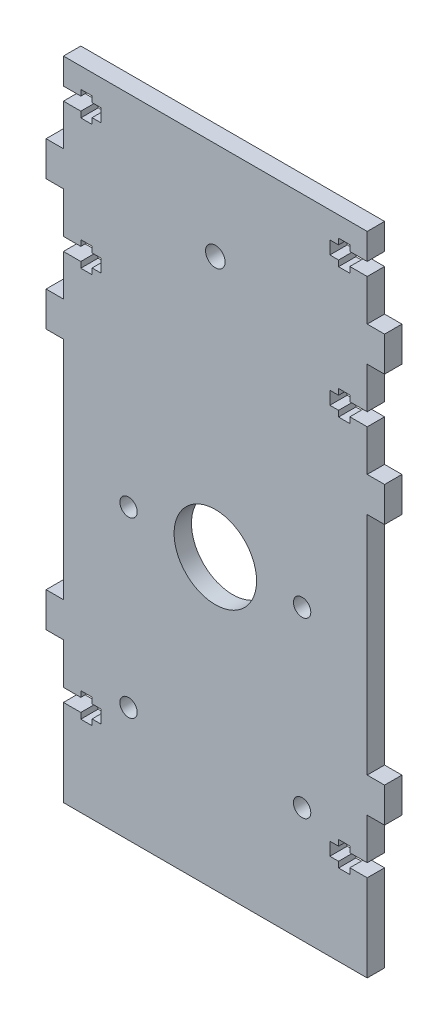
SolidWorks part; units mm, degrees
ref_plane "前视基准面" through (0, 0, 0) normal (0, 0, 1) x (1, 0, 0)
ref_plane "上视基准面" through (0, 0, 0) normal (0, 1, 0) x (1, 0, 0)
ref_plane "右视基准面" through (0, 0, 0) normal (1, 0, 0) x (0, 0, -1)
sketch "草图1" plane through (0, 0, 0) normal (0, 0, 1) x (1, 0, 0)
  line L1 (0, 4.863) -> (-4, 4.863)
  line L2 (-4, 4.863) -> (-4, 12.863)
  line L3 (-4, 12.863) -> (0, 12.863)
  line L5 (0, 22.363) -> (4, 22.363)
  line L6 (4, 22.363) -> (4, 21.013)
  line L7 (4, 21.013) -> (6.6, 21.013)
  line L8 (6.6, 21.013) -> (6.6, 22.363)
  line L9 (6.6, 22.363) -> (8.6, 22.363)
  line L10 (8.6, 22.363) -> (8.6, 25.363)
  line L11 (8.6, 25.363) -> (6.6, 25.363)
  line L12 (6.6, 25.363) -> (6.6, 26.713)
  line L13 (6.6, 26.713) -> (4, 26.713)
  line L14 (4, 26.713) -> (4, 25.363)
  line L15 (4, 25.363) -> (0, 25.363)
  line L16 (0, 25.363) -> (0, 31.363)
  line L17 (0, 31.363) -> (70, 31.363)
  line L18 (0, 25.363) -> (0, 22.363) construction
  line L20 (35, 31.363) -> (35, 28.363) construction
  line L21 (-4, -21.137) -> (0, -21.137) construction
  line L39 (-4, 8.863) -> (74, 8.863) construction
  line L40 (8.6, 23.863) -> (0, 23.863) construction
  line L51 (0, -7.637) -> (0, -4.637) construction
  line L52 (4, -7.637) -> (0, -7.637)
  line L53 (4, -8.987) -> (4, -7.637)
  line L54 (6.6, -8.987) -> (4, -8.987)
  line L55 (6.6, -7.637) -> (6.6, -8.987)
  line L56 (8.6, -7.637) -> (6.6, -7.637)
  line L57 (8.6, -4.637) -> (8.6, -7.637)
  line L58 (6.6, -4.637) -> (8.6, -4.637)
  line L59 (6.6, -3.287) -> (6.6, -4.637)
  line L60 (4, -3.287) -> (6.6, -3.287)
  line L61 (4, -4.637) -> (4, -3.287)
  line L62 (0, -4.637) -> (4, -4.637)
  line L63 (0, -4.637) -> (0, 4.863)
  line L65 (70, -51.137) -> (0, -51.137) construction
  line L83 (0, 22.363) -> (0, 12.863)
  line L84 (8.6, -6.137) -> (6.1425, -6.137) construction
  line L91 (-4, -25.137) -> (0, -25.137)
  line L92 (-4, -17.137) -> (-4, -25.137)
  line L93 (0, -17.137) -> (-4, -17.137)
  line L94 (0, -17.137) -> (0, -7.637)
  line L95 (0, -97.637) -> (4, -97.637)
  line L96 (4, -97.637) -> (4, -98.987)
  line L97 (70, 25.363) -> (70, 31.363)
  line L98 (63.4, 25.363) -> (63.4, 26.713)
  line L99 (63.4, 21.013) -> (63.4, 22.363)
  line L100 (66, 26.713) -> (66, 25.363)
  line L101 (66, 22.363) -> (66, 21.013)
  line L102 (66, 25.363) -> (70, 25.363)
  line L103 (63.4, 26.713) -> (66, 26.713)
  line L104 (61.4, 25.363) -> (63.4, 25.363)
  line L105 (61.4, 22.363) -> (61.4, 25.363)
  line L106 (63.4, 22.363) -> (61.4, 22.363)
  line L107 (66, 21.013) -> (63.4, 21.013)
  line L108 (70, 22.363) -> (66, 22.363)
  line L109 (70, 22.363) -> (70, 12.863)
  line L110 (74, 12.863) -> (70, 12.863)
  line L111 (61.4, -6.137) -> (63.8575, -6.137) construction
  line L112 (70, -7.637) -> (70, -4.637) construction
  line L113 (74, -21.137) -> (70, -21.137) construction
  line L114 (70, -17.137) -> (70, -7.637)
  line L115 (70, -17.137) -> (74, -17.137)
  line L116 (74, -17.137) -> (74, -25.137)
  line L117 (74, -25.137) -> (70, -25.137)
  line L118 (70, -4.637) -> (70, 4.863)
  line L119 (70, -4.637) -> (66, -4.637)
  line L120 (66, -4.637) -> (66, -3.287)
  line L121 (66, -3.287) -> (63.4, -3.287)
  line L122 (63.4, -3.287) -> (63.4, -4.637)
  line L123 (63.4, -4.637) -> (61.4, -4.637)
  line L124 (61.4, -4.637) -> (61.4, -7.637)
  line L125 (61.4, -7.637) -> (63.4, -7.637)
  line L126 (63.4, -7.637) -> (63.4, -8.987)
  line L127 (63.4, -8.987) -> (66, -8.987)
  line L128 (66, -8.987) -> (66, -7.637)
  line L129 (66, -7.637) -> (70, -7.637)
  line L130 (74, 4.863) -> (74, 12.863)
  line L131 (70, 4.863) -> (74, 4.863)
  line L132 (4, -98.987) -> (6.6, -98.987)
  line L133 (0, -25.137) -> (70, -25.137) construction
  line L134 (0, -25.137) -> (0, -96.137) construction
  line L137 (6.6, -98.987) -> (6.6, -97.637)
  line L138 (6.6, -97.637) -> (8.6, -97.637)
  line L139 (8.6, -97.637) -> (8.6, -94.637)
  line L140 (8.6, -94.637) -> (6.6, -94.637)
  line L141 (6.6, -94.637) -> (6.6, -93.287)
  line L142 (6.6, -93.287) -> (4, -93.287)
  line L143 (4, -93.287) -> (4, -94.637)
  line L144 (4, -94.637) -> (0, -94.637)
  line L145 (0, -94.637) -> (0, -97.637) construction
  line L146 (8.6, -96.137) -> (0, -96.137) construction
  line L147 (0, -85.137) -> (-4, -85.137)
  line L148 (-4, -85.137) -> (-4, -77.137)
  line L149 (-4, -77.137) -> (0, -77.137)
  line L150 (0, -94.637) -> (0, -85.137)
  line L151 (0, -25.137) -> (0, -77.137)
  line L152 (0, -97.637) -> (0, -117.637)
  line L153 (70, -25.137) -> (70, -77.137)
  line L154 (61.4, -96.137) -> (70, -96.137) construction
  line L155 (70, -94.637) -> (70, -97.637) construction
  line L156 (70, -97.637) -> (70, -117.637)
  line L157 (70, -94.637) -> (70, -85.137)
  line L158 (74, -77.137) -> (70, -77.137)
  line L159 (74, -85.137) -> (74, -77.137)
  line L160 (70, -85.137) -> (74, -85.137)
  line L161 (66, -94.637) -> (70, -94.637)
  line L162 (66, -93.287) -> (66, -94.637)
  line L163 (63.4, -93.287) -> (66, -93.287)
  line L164 (63.4, -94.637) -> (63.4, -93.287)
  line L165 (61.4, -94.637) -> (63.4, -94.637)
  line L166 (61.4, -97.637) -> (61.4, -94.637)
  line L167 (63.4, -97.637) -> (61.4, -97.637)
  line L168 (63.4, -98.987) -> (63.4, -97.637)
  line L169 (66, -98.987) -> (63.4, -98.987)
  line L170 (66, -97.637) -> (66, -98.987)
  line L171 (70, -97.637) -> (66, -97.637)
  line L172 (0, -117.637) -> (70, -117.637)
  circle A0 centre (35, 8.863) radius 2.25
  circle A1 centre (35, -51.137) radius 9.5
  circle A2 centre (55, -51.137) radius 2
  circle A3 centre (15, -51.137) radius 2
  circle A4 centre (55, -91.137) radius 2
  circle A5 centre (15, -91.137) radius 2
  point P37 (35, -25.6947)
  point P135 (0, 0)
  dimension "D11" = 90
  dimension "D12" = 1.35
  dimension "D14" = 20
  dimension "D15" = 40
  dimension "D1" = 35
  dimension "D2" = 3
  dimension "D3" = 8
  dimension "D4" = 4
  dimension "D5" = 9.5
  dimension "D6" = 4
  dimension "D7" = 2
  dimension "D8" = 2.6
  dimension "D9" = 1.35
  dimension "D10" = 6
  dimension "D13" = 20
extrude "凸台-拉伸1" add sketch "草图1" along normal blind 4
sketch "草图3" plane through (0, 0, 0) normal (-1, 0, 0) x (0, 0, 1)
  line L0 (2, -7.637) -> (2, -4.637)
  line L1 (4, -7.637) -> (0, -7.637) construction
  line L2 (4, -4.637) -> (0, -4.637) construction
  circle A0 centre (2, -6.137) radius 1.5
